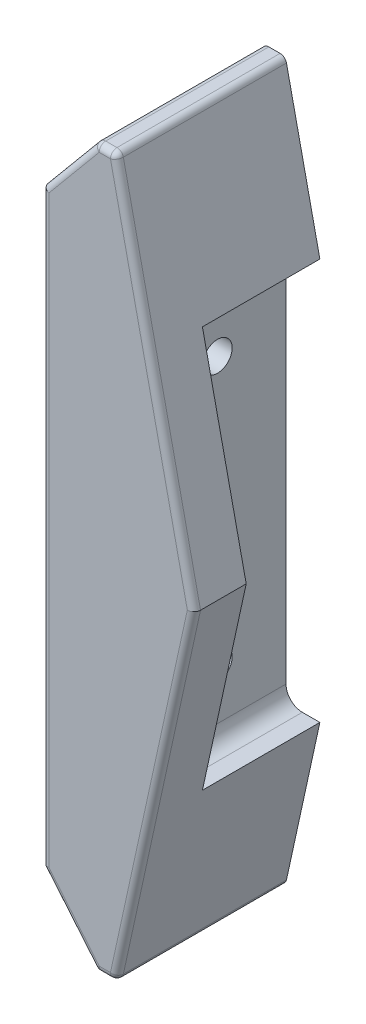
SolidWorks part; units mm, degrees
material "6061 Alloy"
ref_plane "Top Plane" through (0, 0, 0) normal (0, 0, 1) x (1, 0, 0)
ref_plane "Front Plane" through (0, 0, 0) normal (0, 1, 0) x (1, 0, 0)
ref_plane "Right Plane" through (0, 0, 0) normal (1, 0, 0) x (0, 0, -1)
sketch "Sketch1" plane through (0, 0, 0) normal (0, 0, 1) x (1, 0, 0)
  line L0 (-12.5, 43) -> (-2.5, 55)
  line L1 (-12.5, -55) -> (12.5, -55)
  line L2 (-12.5, -55) -> (-12.5, 55)
  line L3 (-12.5, 55) -> (12.5, 55)
  line L4 (12.5, -55) -> (12.5, 55)
  line L5 (-12.5, -55) -> (12.5, 55) construction
  line L6 (-12.5, 55) -> (12.5, -55) construction
  line L7 (-2.5, 55) -> (0.5, 55)
  line L8 (0.5, 55) -> (12.5, 0)
  line L9 (-12.5, 0) -> (12.5, 0) construction
  line L10 (0.5, -55) -> (12.5, 0)
  line L11 (-2.5, -55) -> (0.5, -55)
  line L12 (-12.5, -43) -> (-2.5, -55)
  point P0 (0, 0)
  dimension "D1" = 110
  dimension "D2" = 25
  dimension "D3" = 12
  dimension "D4" = 10
  dimension "D5" = 3
extrude "Main Profile" add sketch "Sketch1" along normal blind 26 contours L2 L12 L1 L10 L8 L3 L0
ref_plane "Plane1" through (12.5, 0, 0) normal (-1, 0, 0) x (0, 0, 1)
sketch "Sketch2" plane through (12.5, 0, 0) normal (-1, 0, 0) x (0, 0, 1)
  line L0 (0, -55) -> (0, 0) construction
  line L1 (26, 0) -> (0, 0) construction
  line L2 (0, -30.75) -> (18, -30.75)
  line L3 (0, -30.75) -> (0, 30.75)
  line L4 (0, 30.75) -> (18, 30.75)
  line L5 (18, -30.75) -> (18, 30.75)
  point P6 (18, 0)
  dimension "D1" = 61.5
  dimension "D2" = 18
extrude "Body Attachment Cavity" cut sketch "Sketch2" along normal blind 11.9
fillet "Fillet1" radius 2.5 2 edges at (0.6, 30.75, 9) (0.6, -30.75, 9)
ref_plane "Face Plane" through (-12.5, 0, 0) normal (-1, 0, 0) x (0, 0, 1)
sketch "Sketch5" plane through (-12.5, 0, 0) normal (-1, 0, 0) x (0, 0, 1)
  line L0 (0, -43) -> (0, 43) construction
  line L1 (0, 41) -> (24, 41)
  line L2 (0, 41) -> (0, -41)
  line L3 (0, -41) -> (24, -41)
  line L4 (24, 41) -> (24, -41)
  point P6 (0, 0)
  dimension "D1" = 82
  dimension "D2" = 24
extrude "Face Cavity" cut sketch "Sketch5" against normal blind 4
fillet "Fillet2" radius 2.5 2 edges at (-10.5, -41, 24) (-10.5, 41, 24)
sketch "Sketch7" plane through (0, 0, 0) normal (0, 0, -1) x (-1, 0, 0)
  line L0 (10.5, 41) -> (1.0773, 52.021)
  line L1 (1.0773, 52.021) -> (1.0773, -52.021)
  line L2 (0, 0) -> (25.381, 0) construction
  line L3 (10.5, -41) -> (1.0773, -52.021)
  line L4 (10.5, -41) -> (10.5, 41)
  line L7 (8.5, 41) -> (12.5, 41) construction
  line L8 (12.5, 43) -> (2.5, 55) construction
  point P8 (1.0773, 0)
  dimension "D1" = 3
  dimension "D2" = 14.5
extrude "Cut-Extrude3" cut sketch "Sketch7" against normal blind 4
fillet "Fillet3" radius 2.5 2 edges at (-1.0773, 52.021, 2) (-1.0773, -52.021, 2)
sketch "Sketch8" plane through (-12.5, 0, 0) normal (-1, 0, 0) x (0, 0, 1)
  line L0 (0, 43) -> (0, 55) construction
  line L1 (0, 49) -> (27.4971, 49)
  line L2 (0, 49) -> (0, -61)
  line L3 (0, -61) -> (27.4971, -61)
  line L4 (27.4971, 49) -> (27.4971, -61)
  dimension "D1" = 110
revolve "Cut-Revolve1" cut sketch "Sketch8" angle 4 about L2
sketch "Sketch9" plane through (0, 0, 4) normal (0, 0, -1) x (-1, 0, 0)
  point P0 (5.25, 40.95)
  point P3 (5.25, -40.95)
hole_wizard "M3x0.5 Tapped Hole1" positions "Sketch9" profile "Sketch10" tap size "M3x0.5" standard "ANSI Metric"
sketch "Sketch10" plane through (-5.25, 40.95, 4) normal (1, 0, 0) x (0, 1, 0)
  line L0 (0, 0) -> (0, 10.7511)
  line L1 (0, 10.7511) -> (1.25, 10)
  line L2 (1.25, 10) -> (1.25, 0)
  line L5 (1.25, 0) -> (0, 0)
  line L10 (0, 10.7511) -> (-1.25, 10) construction
  line L11 (0, -6.35) -> (0, 107.95) construction
  dimension "Tap Drill Dia." = 2.5
  dimension "Tap Drill Depth" = 10
  dimension "Drill Angle" = 118
cosmetic thread "Hole Thread1" parameters "D1"=6, "D2"=3
cosmetic thread "Hole Thread2" parameters "D1"=6, "D2"=3
sketch "Sketch11" plane through (-8.5, 0, 0) normal (-1, 0, 0) x (0, 0, 1)
  line L0 (4, 41) -> (4, -41) construction
  line L1 (4, 0) -> (24, 0) construction
  line L2 (24, 38.5) -> (24, -38.5) construction
  point P0 (10.5, 20.5)
  point P2 (10.5, -20.5)
  dimension "D1" = 6.5
  dimension "D2" = 6.5
  dimension "D3" = 20.5
  dimension "D4" = 20.5
hole_wizard "CSK for M4 Flat Head Machine Screw1" positions "Sketch11" profile "Sketch12" countersink size "M4" standard "ANSI Metric"
sketch "Sketch12" plane through (-8.5, 20.5, 10.5) normal (0, 1, 0) x (0, 0, 1)
  line L0 (0, 0) -> (0, 11.3519)
  line L1 (0, 11.3519) -> (2.25, 10)
  line L2 (2.25, 10) -> (2.25, 2.45)
  line L3 (2.25, 2.45) -> (4.7, 0)
  line L5 (4.7, 0) -> (0, 0)
  line L6 (-2.25, 2.45) -> (-4.7, 0) construction
  line L10 (0, 11.3519) -> (-2.25, 10) construction
  line L11 (0, -6.35) -> (0, 107.95) construction
  dimension "Hole Dia." = 4.5
  dimension "Hole Depth" = 10
  dimension "Near C'Sink Dia." = 9.4
  dimension "Near C'Sink Angle" = 90
  dimension "Drill Angle" = 118
sketch "Sketch13" plane through (0, 0, 18) normal (0, 0, -1) x (-1, 0, 0)
  point P0 (-3.1938, 28.1834)
  point P3 (-3.1938, -28.1834)
hole_wizard "3/32 (0.09375) Diameter Hole1" positions "Sketch13" profile "Sketch14" hole size "3/32" standard "ANSI Inch"
sketch "Sketch14" plane through (3.1938, 28.1834, 18) normal (1, 0, 0) x (0, 1, 0)
  line L0 (0, 0) -> (0, 6)
  line L1 (0, 6) -> (1.1906, 5.2846)
  line L2 (1.1906, 5.2846) -> (1.1906, 0)
  line L5 (1.1906, 0) -> (0, 0)
  line L10 (0, 6) -> (-1.1906, 5.2846) construction
  line L11 (0, -6.35) -> (0, 107.95) construction
  dimension "Hole Dia." = 2.3812
  dimension "Hole Depth" = 6
  dimension "Drill Angle" = 118
fillet "Fillet4" radius 1 11 edges at (-1, 55, 26) (6.5, 27.5, 26) (6.5, -27.5, 26) (-1, -55, 26) (-6.591, -50.0909, 26) (-10.6819, 0, 26) (-6.591, 50.0909, 26) (-2.5, 55, 13) (0.5, 55, 13) (0.5, -55, 13) (-2.5, -55, 13)
